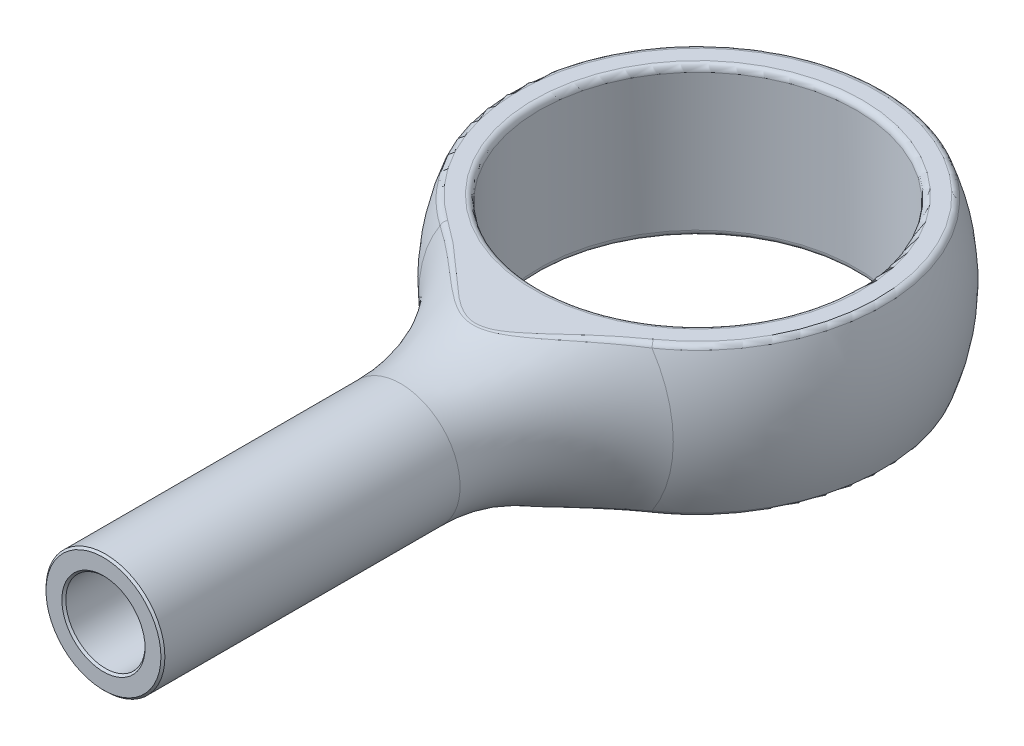
SolidWorks part; units mm, degrees
ref_plane "Front Plane" through (0, 0, 0) normal (0, 0, 1) x (1, 0, 0)
ref_plane "Top Plane" through (0, 0, 0) normal (0, 1, 0) x (1, 0, 0)
ref_plane "Right Plane" through (0, 0, 0) normal (1, 0, 0) x (0, 0, -1)
sketch "Sketch1" plane through (0, 0, 0) normal (0, 1, 0) x (1, 0, 0)
  line L0 (-1.5, -15) -> (1.5, -15)
  line L1 (-1.5, -15) -> (-1.5, -7.5)
  line L2 (1.5, -15) -> (1.5, -7.5)
  circle A0 centre (0, 0) radius 5
  circle A1 centre (0, 0) radius 4
  circle A2 centre (0, 0) radius 2 construction
  arc A3 (-1.5, -7.5) -> (-3.2117, -3.8321) centre (-6.2857, -7.5) ccw
  arc A4 (1.5, -7.5) -> (3.2117, -3.8321) centre (6.2857, -7.5) cw
  point P8 (0, -15)
  point P12 (0, 0)
  point P13 (0, 0)
  dimension "D1" = 10
  dimension "D2" = 8
  dimension "D3" = 4
  dimension "D4" = 15
  dimension "D5" = 3
  dimension "D6" = 7.5
sketch "Sketch2" plane through (0, 0, 0) normal (0, 1, 0) x (1, 0, 0)
  line L0 (-1.5, -15) -> (1.5, -15) construction
  line L1 (-1.5, -15) -> (-1.5, -7.5) construction
  line L2 (-1.5, -15) -> (0, -15)
  line L3 (-1.5, -15) -> (-1.5, -7.5)
  line L4 (0, 5) -> (0, -15)
  arc A0 (-1.5, -7.5) -> (-3.2117, -3.8321) centre (-6.2857, -7.5) ccw construction
  circle A1 centre (0, 0) radius 5 construction
  arc A2 (-1.5, -7.5) -> (-3.2117, -3.8321) centre (-6.2857, -7.5) ccw
  arc A3 (0, 5) -> (-3.2117, -3.8321) centre (0, 0) ccw
revolve "Revolve1" add sketch "Sketch2" angle 360 about L4
sketch "Sketch3" plane through (0, 0, 0) normal (1, 0, 0) x (0, 0, -1)
  line L0 (-23.8038, 13.4875) -> (13.9825, 13.4875)
  line L1 (13.9825, 13.4875) -> (13.9825, 1.875)
  line L2 (13.9825, 1.875) -> (-5.6429, 1.875)
  line L3 (-8.5108, 2.7792) -> (-23.8038, 13.4875)
  line L4 (0, 0) -> (17.771, 0) construction
  line L5 (5, 0) -> (-5, 0) construction
  line L6 (-8.5108, -2.7792) -> (-23.8038, -13.4875)
  line L7 (13.9825, -1.875) -> (-5.6429, -1.875)
  line L8 (13.9825, -13.4875) -> (13.9825, -1.875)
  line L9 (-23.8038, -13.4875) -> (13.9825, -13.4875)
  arc A0 (-5.6429, 1.875) -> (-8.5108, 2.7792) centre (-5.6429, 6.875) cw
  arc A1 (-5.6429, -1.875) -> (-8.5108, -2.7792) centre (-5.6429, -6.875) ccw
  arc A2 (-7.5, 1.5) -> (-3.8321, 3.2117) centre (-7.5, 6.2857) ccw construction
  point P16 (-16.7771, 13.4875)
  point P17 (0, 0)
  point P18 (0, 0)
  dimension "D1" = 5
  dimension "D2" = 145
  dimension "D3" = 3.75
extrude "Cut-Extrude1" cut sketch "Sketch3" against normal mid plane 10
sketch "Sketch5" plane through (0, 0, 0) normal (0, 1, 0) x (1, 0, 0)
  circle A0 centre (0, 0) radius 4 construction
  circle A1 centre (0, 0) radius 4
extrude "Cut-Extrude2" cut sketch "Sketch5" against normal mid plane 10
fillet "Fillet1" radius 0.15 6 edges at (0, 1.875, -4) (0, -1.875, 4) (0, -1.875, -4.6351) (0, 1.875, -4.6351) (0.1829, -1.875, 5.6219) (-0.1829, 1.875, 5.6219)
sketch "Sketch6" plane through (0, 0, 15) normal (0, 0, 1) x (1, 0, 0)
  circle A0 centre (0, 0) radius 1
  dimension "D1" = 2
extrude "Cut-Extrude3" cut sketch "Sketch6" against normal blind 5
chamfer "Chamfer1" distance 0.05 angle 45 2 edges at (-1.5, 0, 15) (1, 0, 15)
